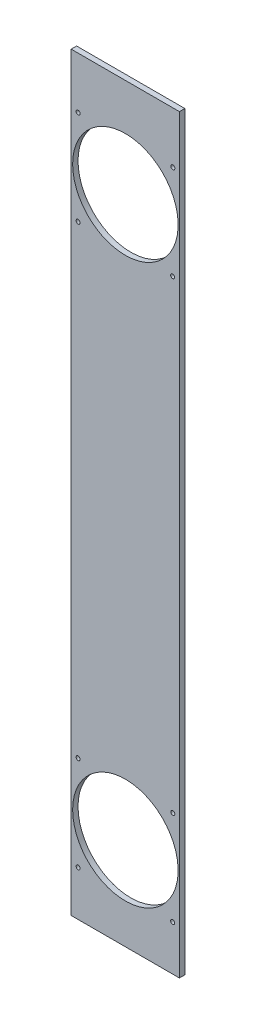
SolidWorks part; units mm, degrees
ref_plane "Plan de face" through (0, 0, 0) normal (0, 0, 1) x (1, 0, 0)
ref_plane "Plan de dessus" through (0, 0, 0) normal (0, 1, 0) x (1, 0, 0)
ref_plane "Plan de droite" through (0, 0, 0) normal (1, 0, 0) x (0, 0, -1)
sketch "Esquisse1" plane through (0, 0, 0) normal (0, 0, 1) x (1, 0, 0)
  line L1 (-60, -416) -> (60, -416)
  line L2 (-60, -416) -> (-60, 416)
  line L3 (-60, 416) -> (60, 416)
  line L4 (60, -416) -> (60, 416)
  line L5 (-60, -416) -> (60, 416) construction
  line L6 (-60, 416) -> (60, -416) construction
  point P0 (0, 0)
  dimension "D1" = 120
  dimension "D2" = 832
extrude "Boss.-Extru.1" add sketch "Esquisse1" along normal blind 6
sketch "Sketch1" plane through (0, 0, 0) normal (0, 0, -1) x (-1, 0, 0)
  circle A0 centre (-0.1, 306.5) radius 58.5
  dimension "D1" = 117
extrude "Cut-Extrude1" cut sketch "Sketch1" against normal blind 10
pattern_linear "LPattern1" count 2 spacing 620 along (0, -1, 0) of "Cut-Extrude1"
hole_wizard "M4 Clearance Hole1" positions "Sketch3" profile "Sketch2" hole size "M4" standard "ANSI Metric"
sketch "Sketch3" plane through (0, 0, 0) normal (0, 0, -1) x (-1, 0, 0)
  point P0 (52.3, 254.1)
  point P3 (52.3, 358.9)
  point P6 (-52.7, 358.9)
  point P9 (-52.5, 254.1)
sketch "Sketch2" plane through (-52.3, 254.1, 0) normal (1, 0, 0) x (0, 1, 0)
  line L0 (0, 0) -> (0, 7.3519)
  line L1 (0, 7.3519) -> (2.25, 6)
  line L2 (2.25, 6) -> (2.25, 0)
  line L5 (2.25, 0) -> (0, 0)
  line L10 (0, 7.3519) -> (-2.25, 6) construction
  line L11 (0, -6.35) -> (0, 107.95) construction
  dimension "Hole Dia." = 4.5
  dimension "Hole Depth" = 6
  dimension "Drill Angle" = 118
pattern_linear "LPattern2" count 2 spacing 620 along (0, -1, 0) of "M4 Clearance Hole1"
